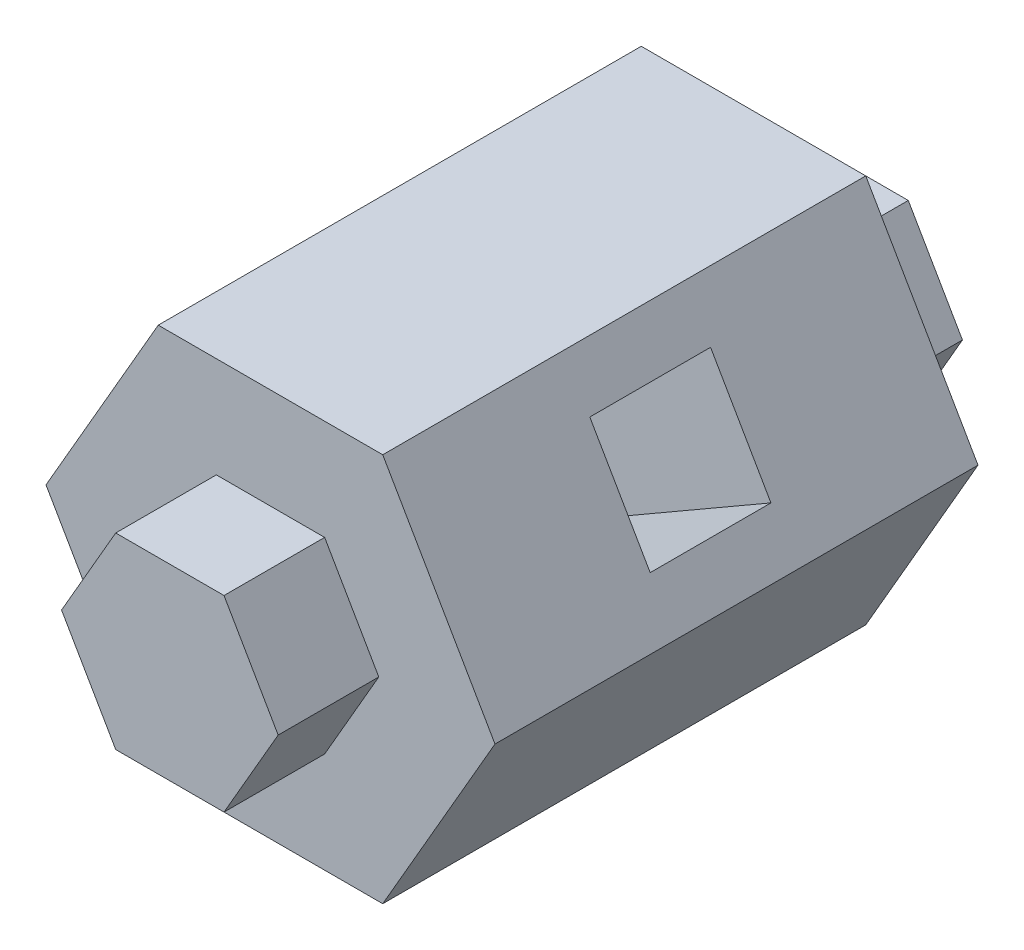
SolidWorks part; units mm, degrees
ref_plane "Plan de face" through (0, 0, 0) normal (0, 0, 1) x (1, 0, 0)
ref_plane "Plan de dessus" through (0, 0, 0) normal (0, 1, 0) x (1, 0, 0)
ref_plane "Plan de droite" through (0, 0, 0) normal (1, 0, 0) x (0, 0, -1)
sketch "Esquisse1" plane through (0, 0, 0) normal (0, 0, 1) x (1, 0, 0)
  line L1 (2.6906, 4.6603) -> (-2.6906, 4.6603)
  line L2 (-2.6906, 4.6603) -> (-5.3812, 0)
  line L3 (-5.3812, 0) -> (-2.6906, -4.6603)
  line L4 (-2.6906, -4.6603) -> (2.6906, -4.6603)
  line L5 (2.6906, -4.6603) -> (5.3812, 0)
  line L6 (5.3812, 0) -> (2.6906, 4.6603)
  line L7 (-5, 8.6603) -> (-10, 0) construction
  line L8 (-10, 0) -> (-5, -8.6603) construction
  line L9 (-5, -8.6603) -> (5, -8.6603) construction
  line L10 (5, -8.6603) -> (10, 0) construction
  line L11 (10, 0) -> (5, 8.6603) construction
  line L12 (5, 8.6603) -> (-5, 8.6603) construction
  circle A0 centre (0, 0) radius 4.6603 construction
  circle A1 centre (0, 0) radius 8.6603 construction
  dimension "D1" = 10
  dimension "D2" = 4
extrude "Boss.-Extru.1" add sketch "Esquisse1" along normal blind 5
sketch "Esquisse2" plane through (0, 0, 0) normal (0, 0, -1) x (-1, 0, 0)
  line L0 (-2.6906, 4.6603) -> (2.6906, 4.6603) construction
  line L1 (5.5774, 9.6603) -> (-5.5774, 9.6603)
  line L2 (-5.5774, 9.6603) -> (-11.1547, 0)
  line L3 (-11.1547, 0) -> (-5.5774, -9.6603)
  line L4 (-5.5774, -9.6603) -> (5.5774, -9.6603)
  line L5 (5.5774, -9.6603) -> (11.1547, 0)
  line L6 (11.1547, 0) -> (5.5774, 9.6603)
  circle A0 centre (0, 0) radius 9.6603 construction
  dimension "D1" = 5
extrude "Boss.-Extru.2" add sketch "Esquisse2" along normal blind 12
sketch "Esquisse4" plane through (-19.5207, 14.4904, 0) normal (0.866, 0.5, 0) x (0, 0, 1)
  line L1 (-12, 25.3094) -> (-9, 25.3094)
  line L2 (-12, 25.3094) -> (-12, 19.3094)
  line L3 (-12, 19.3094) -> (-9, 19.3094)
  line L4 (-9, 25.3094) -> (-9, 19.3094)
  line L6 (28.5682, 22.3094) -> (-28.5682, 22.3094) construction
  point P4 (-8.265, -3)
  point P5 (0, 0)
  point P6 (-2.5412, -3)
  point P7 (0, 0)
  point P9 (0, 0)
  point P10 (-28.5421, 1.5228)
  point P13 (0, 0)
  point P14 (0, 0)
  point P15 (0, 0)
  dimension "D1" = 3
  dimension "D2" = 6
  dimension "D3" = 3
extrude "Enlèv. mat.-Extru.1" cut sketch "Esquisse4" along normal through all and the other way through all
mirror "Symétrie1" about plane through (0, 0, -12) normal (0, 0, -1) of "Boss.-Extru.1", "Enlèv. mat.-Extru.1", "Boss.-Extru.2"
